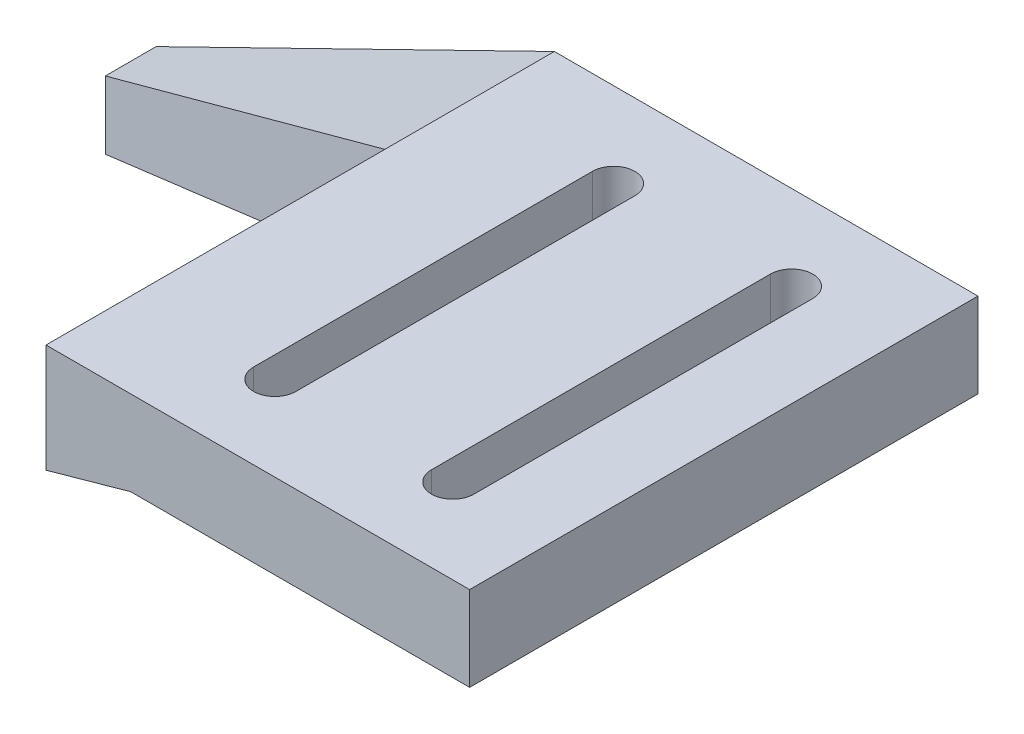
SolidWorks part; units mm, degrees
ref_plane "Alzado" through (0, 0, 0) normal (0, 0, 1) x (1, 0, 0)
ref_plane "Planta" through (0, 0, 0) normal (0, 1, 0) x (1, 0, 0)
ref_plane "Vista lateral" through (0, 0, 0) normal (1, 0, 0) x (0, 0, -1)
sketch "Croquis1" plane through (0, 0, 0) normal (0, 0, 1) x (1, 0, 0)
  line L0 (22.5, 4) -> (-2.5, 4)
  line L1 (22.5, -4) -> (-22.5, -4) construction
  line L2 (22.5, -4) -> (22.5, 4) construction
  line L3 (22.5, 4) -> (-22.5, 4) construction
  line L4 (-22.5, -4) -> (-22.5, 4) construction
  line L5 (22.5, -4) -> (-22.5, 4) construction
  line L6 (22.5, 4) -> (-22.5, -4) construction
  line L7 (22.5, 4) -> (22.5, -1)
  line L8 (22.5, -1) -> (2.5, -1)
  line L9 (2.5, -1) -> (-22.5, -4) construction
  line L10 (-2.5, 4) -> (-22.5, -4)
  line L11 (-22.5, -4) -> (-22.5, -8)
  line L12 (-22.5, -8) -> (2.5, -1)
  line L13 (-2.5, 4) -> (2.5, -1)
  point P0 (0, 0)
  dimension "D1" = 45
  dimension "D2" = 20
  dimension "D3" = 25
  dimension "D4" = 5
  dimension "D5" = 8
  dimension "D6" = 4
extrude "Saliente-Extruir1" add sketch "Croquis1" along normal mid plane 10 contours L13 L10 L11 L12 | L0 L13 L8 L7
sketch "Croquis2" plane through (0, 4, 0) normal (0, 1, 0) x (1, 0, 0)
  line L0 (-26.7833, 0) -> (28.5514, 0) construction
  line L1 (22.5, -5) -> (22.5, 5) construction
  line L2 (6, 0) -> (6, -20) construction
  line L3 (7.25, 0) -> (7.25, -20)
  line L4 (4.75, 0) -> (4.75, -20)
  line L5 (6, 0) -> (16.5, 0) construction
  line L6 (6, 0) -> (16.5, 0) construction
  line L7 (16.5, 0) -> (11.25, 0) construction
  line L8 (11.25, 0) -> (11.25, -9.2362) construction
  line L9 (16.5, 0) -> (16.5, -20) construction
  line L10 (15.25, 0) -> (15.25, -20)
  line L11 (17.75, 0) -> (17.75, -20)
  circle A0 centre (16.5, 0) radius 1.25 construction
  circle A1 centre (6, 0) radius 1.25 construction
  arc A2 (7.25, 0) -> (4.75, 0) centre (6, 0) ccw
  arc A3 (4.75, -20) -> (7.25, -20) centre (6, -20) ccw
  arc A4 (15.25, 0) -> (17.75, 0) centre (16.5, 0) cw
  arc A5 (17.75, -20) -> (15.25, -20) centre (16.5, -20) cw
  point P9 (6, -10)
  point P19 (16.5, -10)
  dimension "D2" = 6
  dimension "D3" = 2.5
  dimension "D1" = 6
  dimension "D4" = 20
sketch "Croquis3" plane through (0, 0, 0) normal (0, 1, 0) x (1, 0, 0)
  line L0 (-22.5, 1.5) -> (-2.5, 5)
  line L1 (-22.5, -5) -> (-22.5, 5) construction
  line L2 (-2.5, 5) -> (-22.5, 5)
  line L3 (-22.5, 5) -> (-22.5, 1.5)
  line L4 (25.4547, 0) -> (-28.4633, 0) construction
  line L5 (-26.7833, 0) -> (28.5514, 0) construction
  line L6 (-2.5, -5) -> (-22.5, -5)
  line L7 (-22.5, -1.5) -> (-2.5, -5)
  line L8 (-22.5, -5) -> (-22.5, -1.5)
  dimension "D1" = 3.5
extrude "Cortar-Extruir1" cut sketch "Croquis3" against normal mid plane 30
sketch "Croquis5" plane through (0, 0, 5) normal (0, 0, 1) x (1, 0, 0)
  line L5 (-2.5, 4) -> (-2.5, -2.4)
  line L6 (-2.5, -2.4) -> (2.5, -1)
  line L7 (2.5, -1) -> (22.5, -1)
  line L8 (22.5, -1) -> (22.5, 4)
  line L10 (-2.5, 4) -> (-2.5, -2.4)
  line L11 (-2.5, -2.4) -> (2.5, -1)
  line L12 (2.5, -1) -> (22.5, -1)
  line L15 (22.5, -1) -> (22.5, 4)
  line L17 (22.5, 4) -> (-2.5, 4)
  line L18 (22.5, 4) -> (-2.5, 4)
  dimension "D1" = 0
extrude "Saliente-Extruir2" add sketch "Croquis5" along normal blind 20
extrude "Cortar-Extruir2" cut sketch "Croquis2" against normal blind 30
